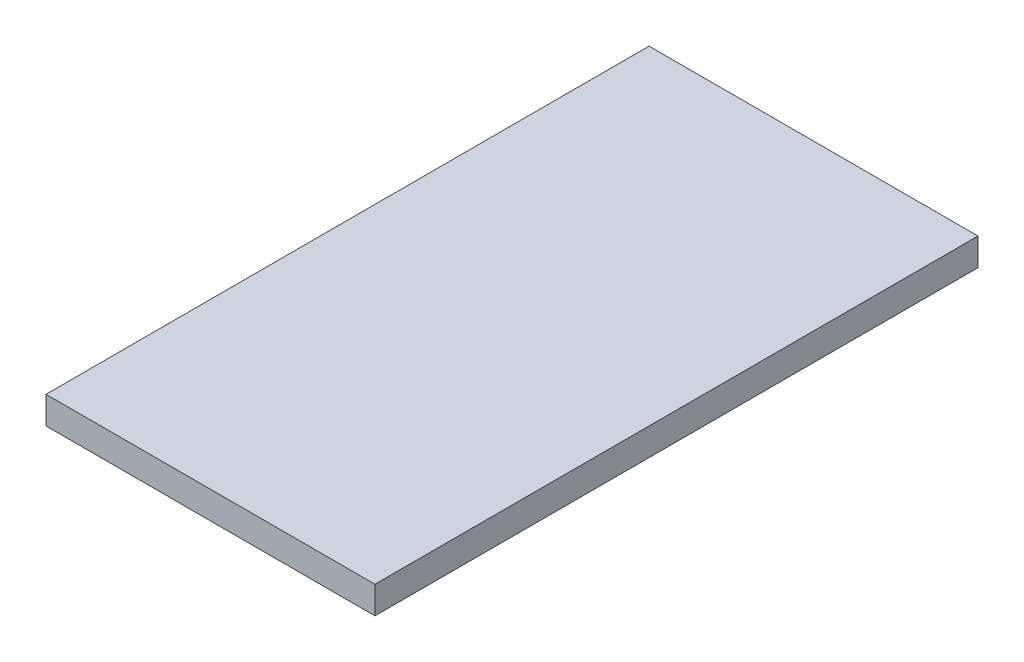
SolidWorks part; units mm, degrees
material "Beech"
ref_plane "Front Plane" through (0, 0, 0) normal (0, 0, 1) x (1, 0, 0)
ref_plane "Top Plane" through (0, 0, 0) normal (0, 1, 0) x (1, 0, 0)
ref_plane "Right Plane" through (0, 0, 0) normal (1, 0, 0) x (0, 0, -1)
sketch "Sketch1" plane through (0, 0, 0) normal (0, 1, 0) x (1, 0, 0)
  line L1 (0, 0) -> (304.8, 0)
  line L2 (0, 0) -> (0, 304.8)
  line L3 (0, 304.8) -> (304.8, 304.8)
  line L4 (304.8, 0) -> (304.8, 304.8)
  dimension "D1" = 304.8
  dimension "D2" = 304.8
extrude "Boss-Extrude1" add sketch "Sketch1" along normal blind 6.35
sketch "Sketch2" plane through (0, 6.35, 0) normal (0, 1, 0) x (1, 0, 0)
  line L1 (304.8, 304.8) -> (0, 304.8) construction
  line L2 (76.2, 304.8) -> (76.2, 165.1)
  line L3 (76.2, 165.1) -> (0, 165.1)
  line L4 (0, 304.8) -> (0, 0) construction
  line L6 (0, 165.1) -> (0, 0)
  line L7 (0, 0) -> (304.8, 0)
  line L8 (304.8, 0) -> (304.8, 304.8)
  line L9 (304.8, 304.8) -> (76.2, 304.8)
  dimension "D1" = 76.2
extrude "Cut-Extrude2" cut sketch "Sketch2" against normal blind 6.35 contours L3 L6 L7 L8 L9 L2
